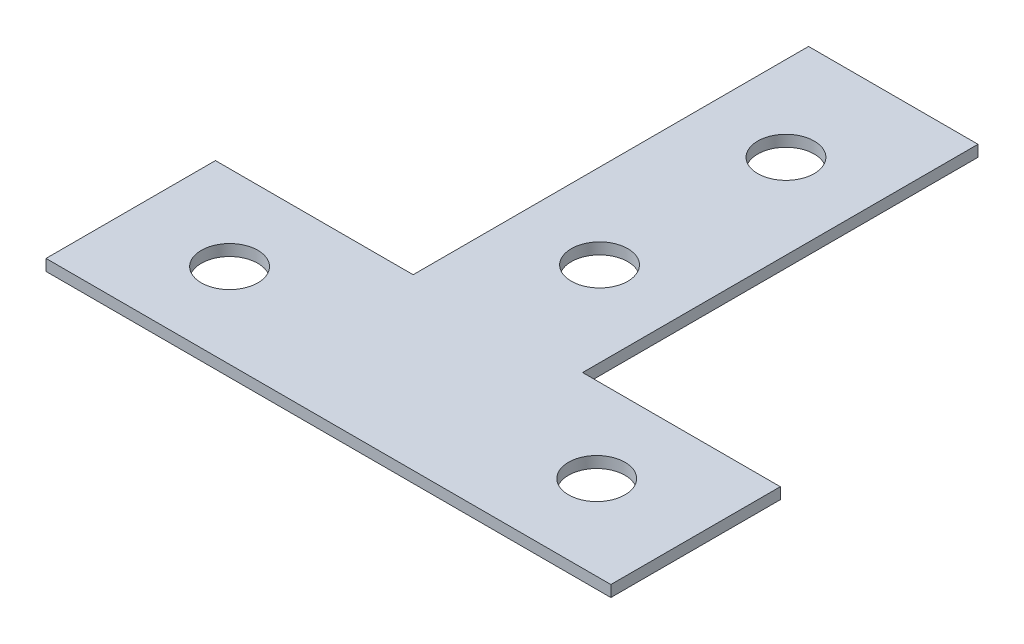
SolidWorks part; units mm, degrees
ref_plane "Front Plane" through (0, 0, 0) normal (0, 0, 1) x (1, 0, 0)
ref_plane "Top Plane" through (0, 0, 0) normal (0, 1, 0) x (1, 0, 0)
ref_plane "Right Plane" through (0, 0, 0) normal (1, 0, 0) x (0, 0, -1)
sketch "Sketch1" plane through (0, 0, 0) normal (0, 1, 0) x (1, 0, 0)
  line L1 (17.5, 50) -> (32.5, 50)
  line L2 (32.5, 50) -> (32.5, 15)
  line L3 (32.5, 15) -> (50, 15)
  line L4 (50, 15) -> (50, 0)
  line L5 (50, 0) -> (0, 0)
  line L6 (0, 15) -> (0, 0)
  line L7 (17.5, 15) -> (0, 15)
  line L8 (17.5, 50) -> (17.5, 15)
  point P0 (25.3753, 67.0213)
  dimension "D1" = 50
  dimension "D2" = 15
  dimension "D3" = 17.5
  dimension "D4" = 35
extrude "Boss-Extrude1" add sketch "Sketch1" along normal blind 1
sketch "Sketch2" plane through (0, 1, 0) normal (0, 1, 0) x (1, 0, 0)
  line L0 (0, 15) -> (0, 0) construction
  line L1 (0, 0) -> (50, 0) construction
  circle A0 centre (41.25, 7.5) radius 2.5
  circle A1 centre (25, 40.5) radius 2.5
  circle A2 centre (25, 24) radius 2.5
  circle A3 centre (8.75, 7.5) radius 2.5
  point P12 (0, 0)
  dimension "D1" = 5
  dimension "D2" = 5
  dimension "D3" = 5
  dimension "D4" = 5
  dimension "D5" = 8.75
  dimension "D6" = 41.25
  dimension "D7" = 7.5
  dimension "D8" = 7.5
  dimension "D9" = 25
  dimension "D10" = 24
  dimension "D11" = 40.5
  dimension "D12" = 16.5
extrude "Cut-Extrude1" cut sketch "Sketch2" against normal through all both and the other way through all
